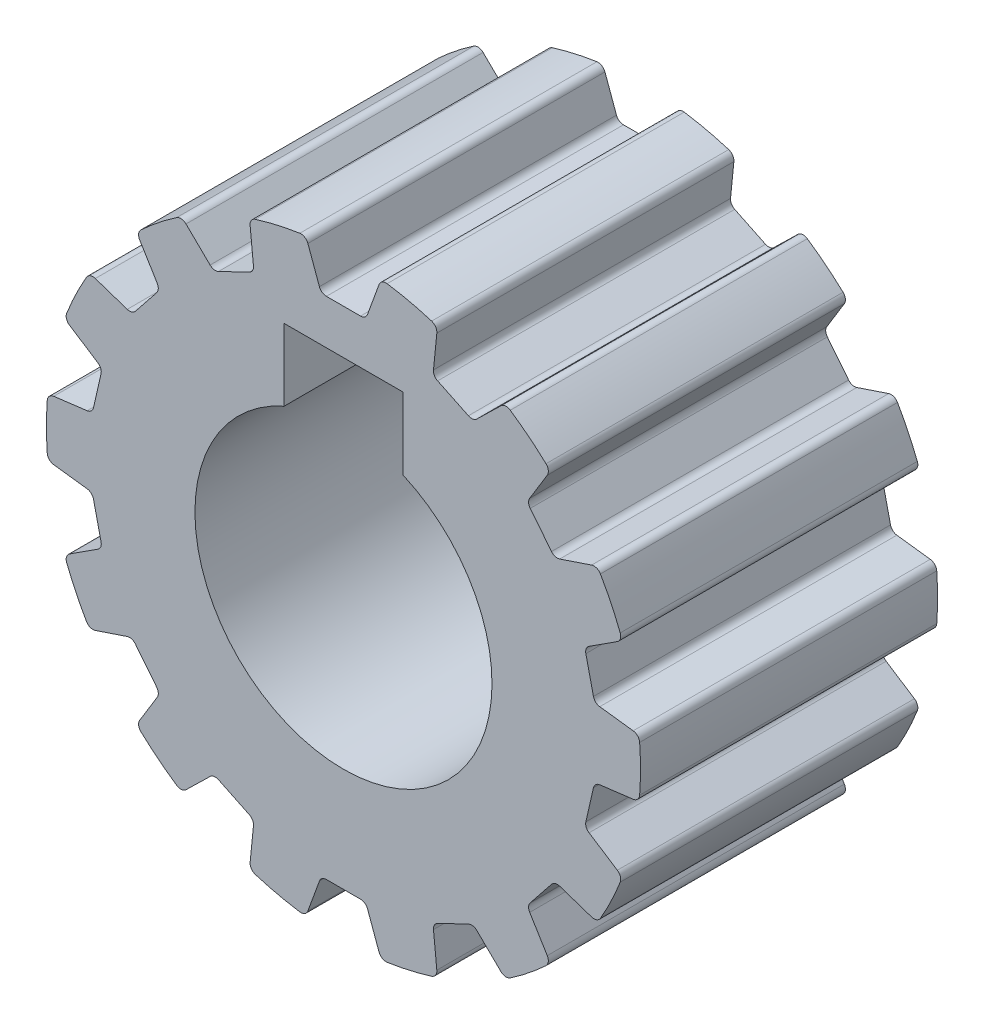
SolidWorks part; units mm, degrees
ref_plane "Front Plane" through (0, 0, 0) normal (0, 0, 1) x (1, 0, 0)
ref_plane "Top Plane" through (0, 0, 0) normal (0, 1, 0) x (1, 0, 0)
ref_plane "Right Plane" through (0, 0, 0) normal (1, 0, 0) x (0, 0, -1)
sketch "Sketch1" plane through (0, 0, 0) normal (0, 0, 1) x (1, 0, 0)
  line L0 (0, 0) -> (0, 2.9546) construction
  line L1 (0, 2.9546) -> (0, 6.9701) construction
  line L2 (-2, 7) -> (2, 7)
  line L3 (-2, 7) -> (-2, 4.5826)
  line L5 (2, 7) -> (2, 4.5826)
  circle A0 centre (0, 0) radius 10
  arc A1 (-2, 4.5826) -> (2, 4.5826) centre (0, 0) ccw
  dimension "D1" = 10
  dimension "D2" = 20
  dimension "D3" = 4
  dimension "D4" = 7
extrude "Boss-Extrude1" add sketch "Sketch1" along normal blind 10
sketch "Sketch2" plane through (0, 0, 10) normal (0, 0, 1) x (1, 0, 0)
  line L0 (0, 0) -> (0, 10) construction
  line L1 (-1.2666, 9.9195) -> (-0.75, 8.5)
  line L2 (-0.75, 8.5) -> (0.75, 8.5)
  line L3 (0.75, 8.5) -> (1.2666, 9.9195)
  circle A0 centre (0, 0) radius 10 construction
  circle M5 centre (0, 0) radius 10
  dimension "D1" = 20
  dimension "D2" = 1.5
  dimension "D3" = 8.5
extrude "Cut-Extrude1" cut sketch "Sketch2" against normal blind 10 and the other way through all contours L0 L2 L3 M5 | L2 L0 L1 M5
pattern_circular "CirPattern1" count 14 over 360 about axis through (0, 0, 0) along (0, 0, 1) of "Cut-Extrude1"
fillet "Fillet2" radius 0.25 56 edges at (-8.5451, 5.1944, 5) (-9.3889, 3.4422, 5) (-8.12, 2.6226, 5) (-8.4538, 1.1602, 5) (-9.9526, 0.9724, 5) (-9.9526, -0.9724, 5) (-8.4538, -1.1602, 5) (-8.12, -2.6226, 5) (-9.3889, -3.4422, 5) (-8.5451, -5.1944, 5) (-7.1132, -4.7133, 5) (-6.178, -5.886, 5) (-6.9656, -7.175, 5) (-5.4451, -8.3875, 5) (-4.3637, -7.3328, 5) (-3.0123, -7.9836, 5) (-3.1627, -9.4867, 5) (-1.2666, -9.9195, 5) (-0.75, -8.5, 5) (0.75, -8.5, 5) (1.2666, -9.9195, 5) (3.1627, -9.4867, 5) (3.0123, -7.9836, 5) (4.3637, -7.3328, 5) (5.4451, -8.3875, 5) (6.9656, -7.175, 5) (6.178, -5.886, 5) (7.1132, -4.7133, 5) (8.5451, -5.1944, 5) (9.3889, -3.4422, 5) (8.12, -2.6226, 5) (8.4538, -1.1602, 5) (9.9526, -0.9724, 5) (9.9526, 0.9724, 5) (8.4538, 1.1602, 5) (8.12, 2.6226, 5) (9.3889, 3.4422, 5) (8.5451, 5.1944, 5) (7.1132, 4.7133, 5) (6.178, 5.886, 5) (6.9656, 7.175, 5) (5.4451, 8.3875, 5) (4.3637, 7.3328, 5) (3.0123, 7.9836, 5) (3.1627, 9.4867, 5) (0.75, 8.5, 5) (-0.75, 8.5, 5) (-3.1627, 9.4867, 5) (-3.0123, 7.9836, 5) (-4.3637, 7.3328, 5) (-5.4451, 8.3875, 5) (-6.9656, 7.175, 5) (-6.178, 5.886, 5) (-7.1132, 4.7133, 5)
